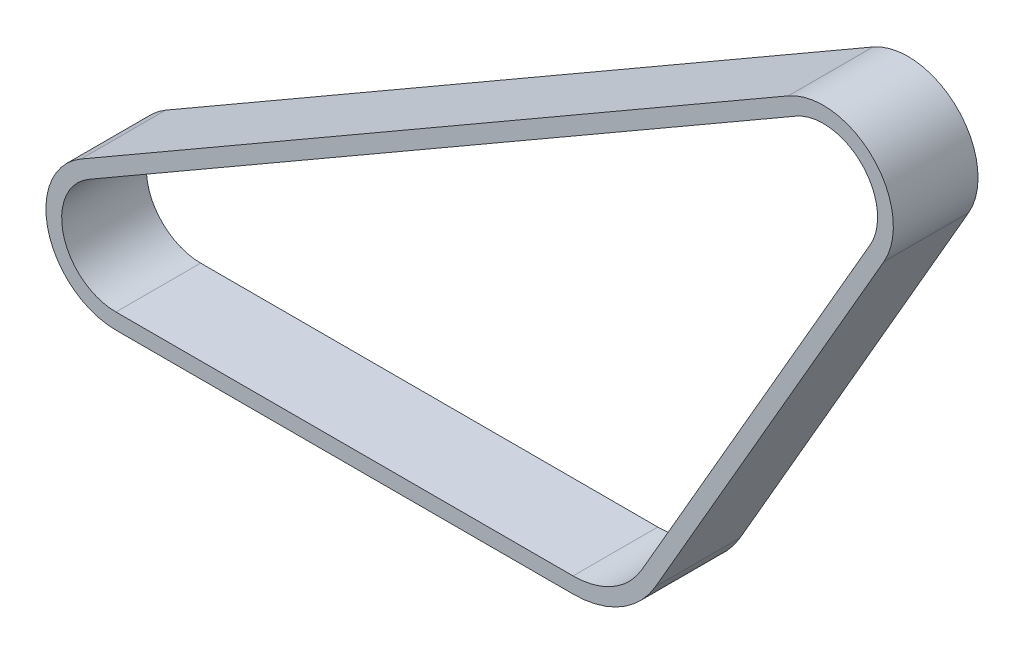
SolidWorks part; units mm, degrees
material "Silicon Rubber"
ref_plane "Front Plane" through (0, 0, 0) normal (0, 0, 1) x (1, 0, 0)
ref_plane "Top Plane" through (0, 0, 0) normal (0, 1, 0) x (1, 0, 0)
ref_plane "Right Plane" through (0, 0, 0) normal (1, 0, 0) x (0, 0, -1)
sketch "Sketch1" plane through (0, 0, 0) normal (0, 0, 1) x (1, 0, 0)
  line L2 (-92.202, -16) -> (0, -16)
  line L3 (-97.6789, 4.44) -> (44.9943, 86.8124)
  line L4 (59.9574, 71.8493) -> (13.8564, -8)
  line L5 (43.4068, 89.562) -> (-99.2664, 7.1896)
  line L6 (-92.202, -19.175) -> (0, -19.175)
  line L7 (16.606, -9.5875) -> (62.707, 70.2618)
  arc A0 (0, -16) -> (13.8564, -8) centre (0, 0) ccw
  arc A1 (59.9574, 71.8493) -> (44.9943, 86.8124) centre (50.4712, 77.3261) ccw
  arc A2 (-97.6789, 4.44) -> (-92.202, -16) centre (-92.202, -5.0463) ccw
  arc A3 (-99.2664, 7.1896) -> (-92.202, -19.175) centre (-92.202, -5.0463) ccw
  arc A4 (0, -19.175) -> (16.606, -9.5875) centre (0, 0) ccw
  arc A5 (62.707, 70.2618) -> (43.4068, 89.562) centre (50.4712, 77.3261) ccw
  dimension "D1" = 32
  dimension "D5" = 21.9075
  dimension "D6" = 170.9307
  dimension "D2" = 120
  dimension "D3" = 92.202
  dimension "D4" = 3.175
extrude "Boss-Extrude1" add sketch "Sketch1" along normal blind 17.0815
